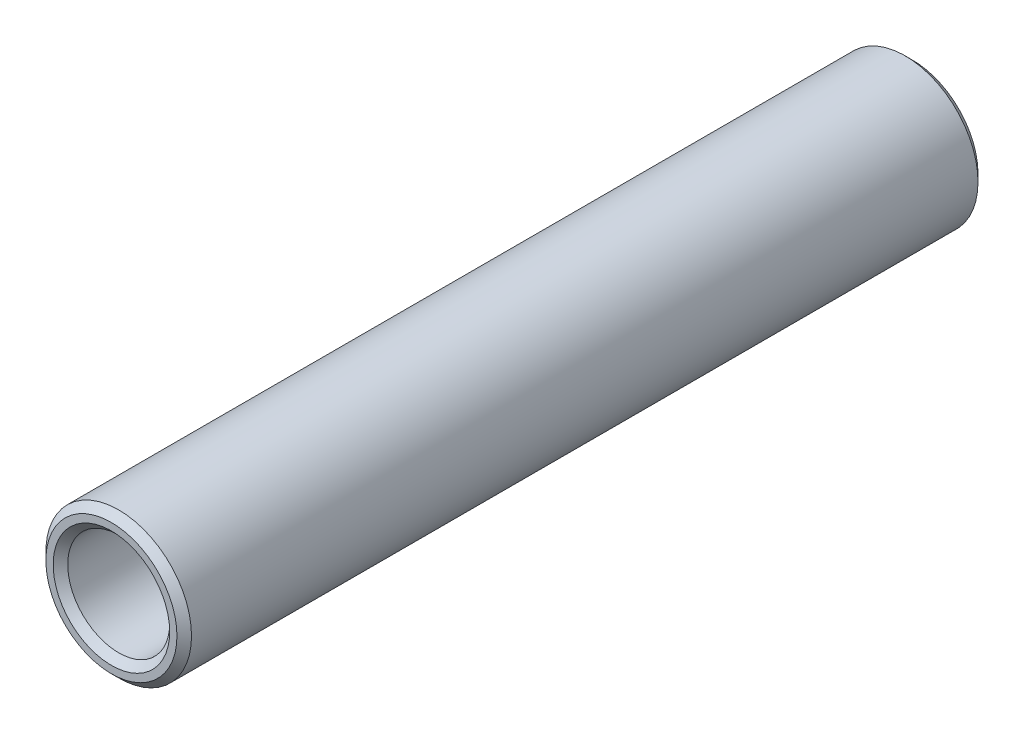
SolidWorks part; units mm, degrees
ref_plane "Ebene vorne" through (0, 0, 0) normal (0, 0, 1) x (1, 0, 0)
ref_plane "Ebene oben" through (0, 0, 0) normal (0, 1, 0) x (1, 0, 0)
ref_plane "Ebene rechts" through (0, 0, 0) normal (1, 0, 0) x (0, 0, -1)
sketch "Skizze1" plane through (0, 0, 0) normal (0, 0, 1) x (1, 0, 0)
  circle A0 centre (0, 0) radius 3.5
  circle A1 centre (0, 0) radius 5
  dimension "D1" = 10
  dimension "D2" = 7
extrude "Aufsatz-Linear austragen1" add sketch "Skizze1" along normal blind 55
chamfer "Fase1" distance 0.5 angle 45 4 edges at (3.5, 0, 0) (5, 0, 0) (5, 0, 55) (3.5, 0, 55)
